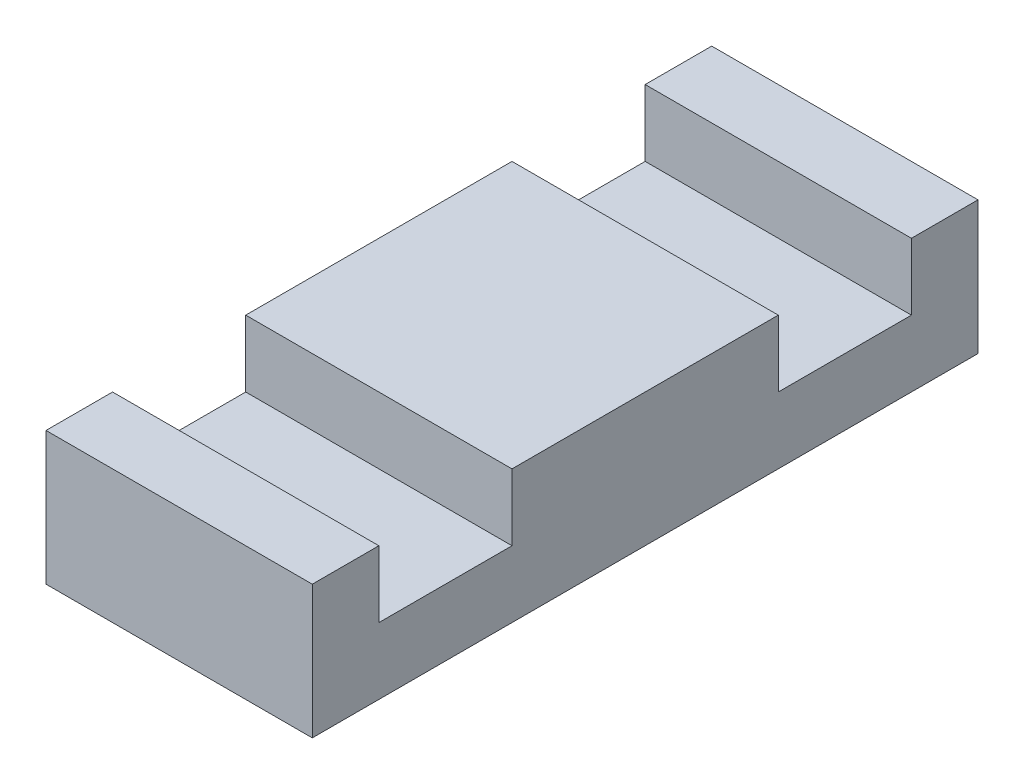
SolidWorks part; units mm, degrees
ref_plane "Front Plane" through (0, 0, 0) normal (0, 0, 1) x (1, 0, 0)
ref_plane "Top Plane" through (0, 0, 0) normal (0, 1, 0) x (1, 0, 0)
ref_plane "Right Plane" through (0, 0, 0) normal (1, 0, 0) x (0, 0, -1)
sketch "Sketch1" plane through (0, 0, 0) normal (0, 1, 0) x (1, 0, 0)
  line L1 (-12.7, -31.75) -> (12.7, -31.75)
  line L2 (-12.7, -31.75) -> (-12.7, 31.75)
  line L3 (-12.7, 31.75) -> (12.7, 31.75)
  line L4 (12.7, -31.75) -> (12.7, 31.75)
  line L5 (-12.7, -31.75) -> (12.7, 31.75) construction
  line L6 (-12.7, 31.75) -> (12.7, -31.75) construction
  point P0 (0, 0)
  dimension "D1" = 63.5
  dimension "D2" = 25.4
extrude "Boss-Extrude1" add sketch "Sketch1" along normal blind 12.7
sketch "Sketch2" plane through (0, 12.7, 0) normal (0, 1, 0) x (1, 0, 0)
  line L0 (-12.7, 31.75) -> (-12.7, -31.75) construction
  line L1 (-12.7, 25.4) -> (12.7, 25.4)
  line L2 (-12.7, 25.4) -> (-12.7, 12.7)
  line L3 (-12.7, 12.7) -> (12.7, 12.7)
  line L4 (12.7, 25.4) -> (12.7, 12.7)
  line L5 (12.7, -31.75) -> (12.7, 31.75) construction
  line L6 (-12.7, -31.75) -> (12.7, -31.75) construction
  line L7 (-12.7, -12.7) -> (12.7, -12.7)
  line L8 (-12.7, -12.7) -> (-12.7, -25.4)
  line L9 (-12.7, -25.4) -> (12.7, -25.4)
  line L10 (12.7, -12.7) -> (12.7, -25.4)
  dimension "D1" = 25.4
  dimension "D2" = 12.7
  dimension "D3" = 12.7
  dimension "D4" = 6.35
extrude "Cut-Extrude1" cut sketch "Sketch2" against normal blind 6.35
